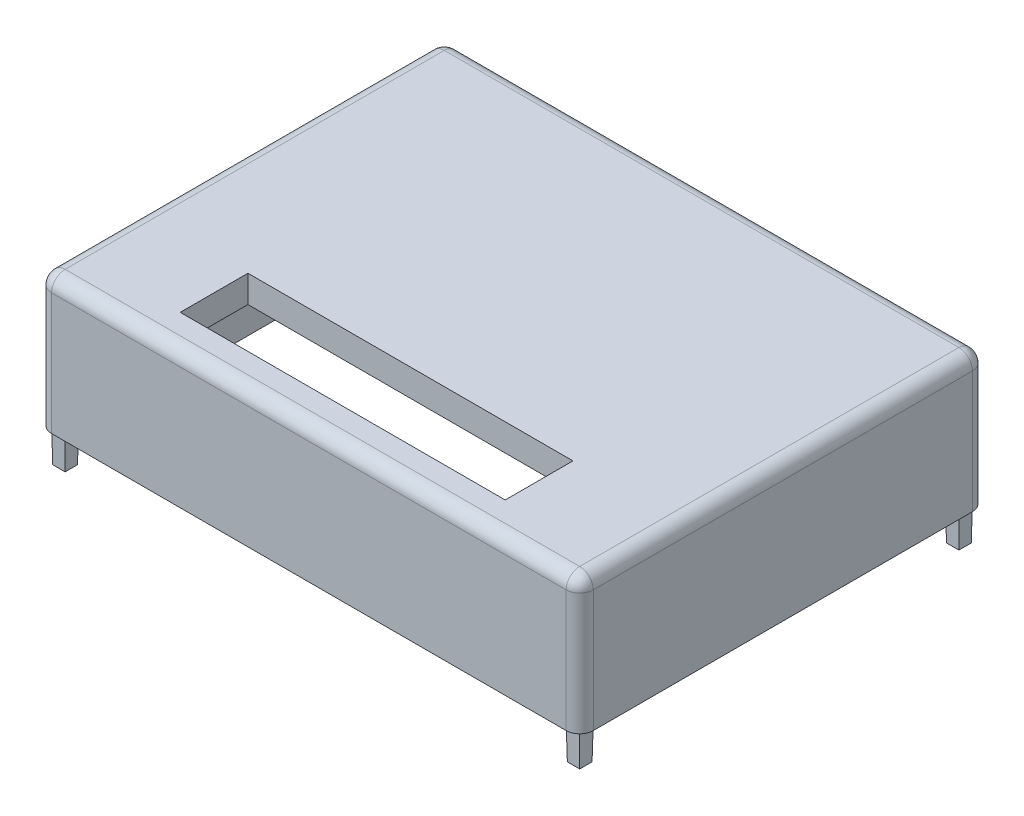
SolidWorks part; units mm, degrees
ref_plane "前视基准面" through (0, 0, 0) normal (0, 0, 1) x (1, 0, 0)
ref_plane "上视基准面" through (0, 0, 0) normal (0, 1, 0) x (1, 0, 0)
ref_plane "右视基准面" through (0, 0, 0) normal (1, 0, 0) x (0, 0, -1)
other "Configuration Table"
sketch "Sketch1" plane through (0, 0, 0) normal (0, 1, 0) x (1, 0, 0)
  line L1 (-50.8, 38.1) -> (50.8, 38.1)
  line L2 (-50.8, 38.1) -> (-50.8, -38.1)
  line L3 (-50.8, -38.1) -> (50.8, -38.1)
  line L4 (50.8, 38.1) -> (50.8, -38.1)
  line L5 (0, -38.1) -> (0, 38.1) construction
  line L6 (-50.8, 0) -> (50.8, 0) construction
  point P0 (0, 0)
  dimension "D1" = 101.6
  dimension "D2" = 76.2
extrude "Boss-Extrude1" add sketch "Sketch1" along normal blind 25.4
sketch "Sketch5" plane through (0, 0, 0) normal (0, -1, 0) x (1, 0, 0)
  line L1 (-45.72, 35.56) -> (45.72, 35.56)
  line L2 (-45.72, 35.56) -> (-45.72, -35.56)
  line L3 (-45.72, -35.56) -> (45.72, -35.56)
  line L4 (45.72, 35.56) -> (45.72, -35.56)
  line L5 (0, -35.56) -> (0, 35.56) construction
  line L6 (-45.72, 0) -> (45.72, 0) construction
  point P0 (0, 0)
  dimension "D1" = 91.44
  dimension "D2" = 71.12
extrude "Cut-Extrude1" cut sketch "Sketch5" against normal blind 20.32
fillet "Fillet1" radius 2.54 8 edges at (50.8, 12.7, 38.1) (-50.8, 12.7, -38.1) (50.8, 12.7, -38.1) (-50.8, 12.7, 38.1) (0, 25.4, -38.1) (-50.8, 25.4, 0) (50.8, 25.4, 0) (0, 25.4, 38.1)
sketch "Sketch7" plane through (0, 0, 0) normal (0, -1, 0) x (-1, 0, 0)
  line L0 (45.72, -35.56) -> (45.72, 35.56) construction
  line L1 (49.53, -36.83) -> (46.99, -36.83)
  line L2 (49.53, -36.83) -> (49.53, -34.29)
  line L3 (49.53, -34.29) -> (46.99, -34.29)
  line L4 (46.99, -36.83) -> (46.99, -34.29)
  line L5 (48.26, -34.29) -> (48.26, -36.83) construction
  line L6 (49.53, -35.56) -> (46.99, -35.56) construction
  line L8 (-45.72, -35.56) -> (45.72, -35.56) construction
  point P0 (48.26, -35.56)
  dimension "D1" = 2.54
  dimension "D2" = 2.54
  dimension "D3" = 2.54
extrude "Boss-Extrude2" add sketch "Sketch7" along normal blind 6.35 draft 1
mirror "Mirror3" about plane through (0, 0, 0) normal (1, 0, 0) of "Boss-Extrude2"
mirror "Mirror4" about plane through (0, 0, 0) normal (0, 0, 1) of "Mirror3", "Boss-Extrude2"
sketch "Sketch8" plane through (0, 25.4, 0) normal (0, 1, 0) x (1, 0, 0)
  line L1 (-30.48, -19.05) -> (30.48, -19.05)
  line L2 (-30.48, -19.05) -> (-30.48, -31.75)
  line L3 (-30.48, -31.75) -> (30.48, -31.75)
  line L4 (30.48, -19.05) -> (30.48, -31.75)
  line L5 (0, -31.75) -> (0, -19.05) construction
  line L6 (-30.48, -25.4) -> (30.48, -25.4) construction
  point P0 (0, -25.4)
  point P4 (1.0247, -22.288)
  dimension "D1" = 60.96
  dimension "D2" = 12.7
  dimension "D3" = 25.4
extrude "Cut-Extrude2" cut sketch "Sketch8" against normal through all
sketch "Sketch9" plane through (0, 0, 35.56) normal (0, 0, -1) x (-1, 0, 0)
  line L0 (-45.72, 20.32) -> (45.72, 20.32) construction
  line L1 (-25.4, 20.32) -> (25.4, 20.32)
  line L2 (-25.4, 20.32) -> (-25.4, 0)
  line L3 (-25.4, 0) -> (25.4, 0)
  line L4 (25.4, 20.32) -> (25.4, 0)
  line L5 (-45.72, 0) -> (45.72, 0) construction
  point P8 (-26.0836, 0)
  point P9 (21.5135, 0)
  dimension "D1" = 50.8
extrude "Boss-Extrude3" add sketch "Sketch9" along normal blind 2.54
